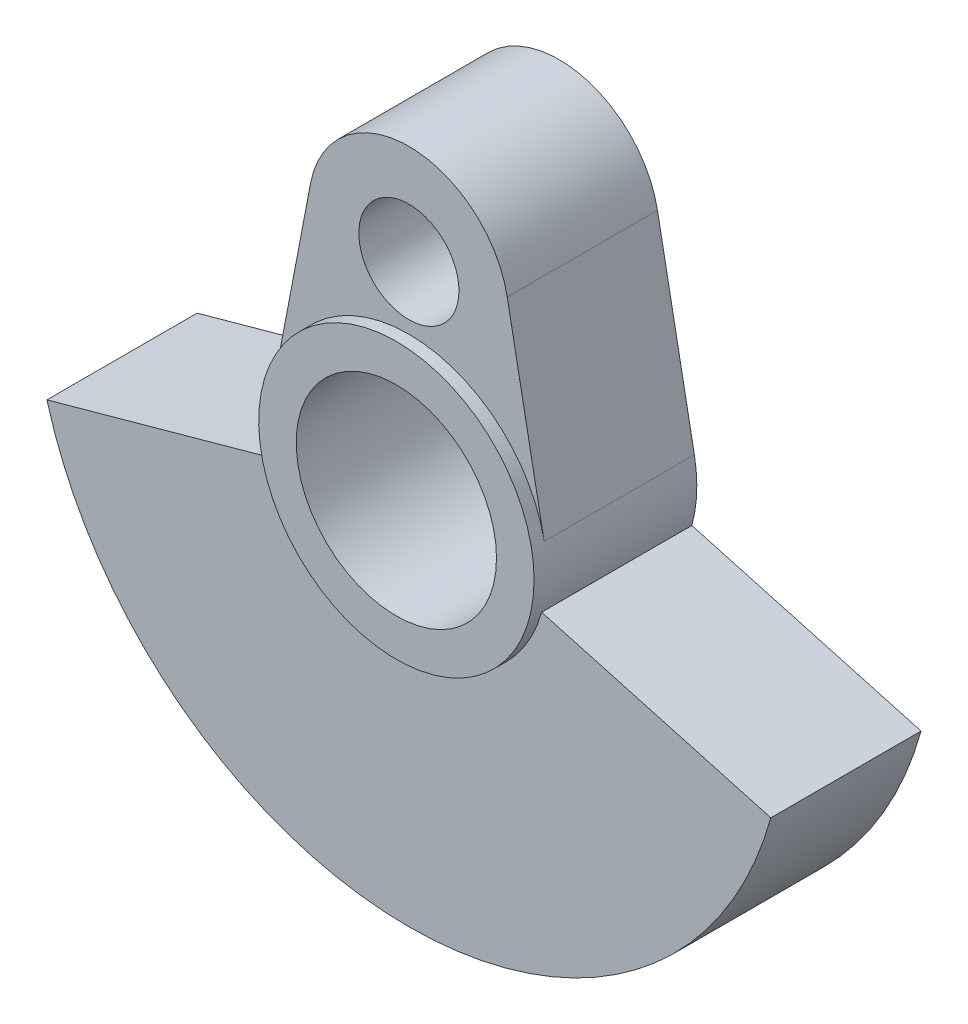
SolidWorks part; units mm, degrees
ref_plane "Front Plane" through (0, 0, 0) normal (0, 0, 1) x (1, 0, 0)
ref_plane "Top Plane" through (0, 0, 0) normal (0, 1, 0) x (1, 0, 0)
ref_plane "Right Plane" through (0, 0, 0) normal (1, 0, 0) x (0, 0, -1)
sketch "Sketch1" plane through (0, 0, 0) normal (0, 0, 1) x (1, 0, 0)
  line L0 (0, 0) -> (0, -8) construction
  line L1 (-5.4025, -6.9688) -> (-3.9291, 0.75)
  line L2 (5.4025, -6.9687) -> (3.9291, 0.75)
  circle A0 centre (0, 0) radius 2
  circle A1 centre (0, -8) radius 4
  arc A2 (3.9291, 0.75) -> (-3.9291, 0.75) centre (0, 0) ccw
  arc A3 (-5.4025, -6.9688) -> (5.4025, -6.9687) centre (0, -8) ccw
  dimension "D1" = 4
  dimension "D3" = 8
  dimension "D4" = 8
  dimension "D5" = 11
  dimension "D2" = 8
extrude "Boss-Extrude1" add sketch "Sketch1" along normal blind 6
sketch "Sketch2" plane through (0, 0, 6) normal (0, 0, 1) x (1, 0, 0)
  line L2 (-14.4568, -12) -> (-5.3008, -9.4667)
  line L5 (0, -30.8989) -> (0, -13.5) construction
  line L7 (14.4568, -12) -> (5.3008, -9.4667)
  line L10 (5.4025, -6.9687) -> (3.9291, 0.75)
  line L11 (-3.9291, 0.75) -> (-5.4025, -6.9688)
  arc A2 (-14.4568, -12) -> (14.4568, -12) centre (0, -8) ccw
  arc A3 (-5.3008, -9.4667) -> (5.3008, -9.4667) centre (0, -8) ccw
  arc A4 (-5.4025, -6.9688) -> (5.4025, -6.9687) centre (0, -8) ccw construction
  arc A7 (-5.4025, -6.9688) -> (5.4025, -6.9687) centre (0, -8) ccw
  arc A8 (3.9291, 0.75) -> (-3.9291, 0.75) centre (0, 0) ccw
  arc A9 (-5.3008, -9.4667) -> (5.3008, -9.4667) centre (0, -8) ccw
  point P7 (0, -8)
  point P13 (0, -8)
  arc M15 (-5.4025, -6.9688) -> (5.4025, -6.9687) centre (0, -8) ccw
  dimension "D1" = 30
  dimension "D2" = 19.8593
  dimension "D3" = 0
extrude "Boss-Extrude2" add sketch "Sketch2" against normal blind 6 contours L5 A2 L7 A9 | A2 L5 L2 M15
sketch "Sketch3" plane through (0, 0, 6) normal (0, 0, 1) x (1, 0, 0)
  circle A0 centre (0, -8) radius 5.5
  arc A1 (-5.4025, -6.9688) -> (-5.3008, -9.4667) centre (0, -8) ccw construction
  circle A2 centre (0, -8) radius 4
  circle A3 centre (0, -8) radius 4 construction
extrude "Boss-Extrude4" add sketch "Sketch3" along normal blind 0.5
